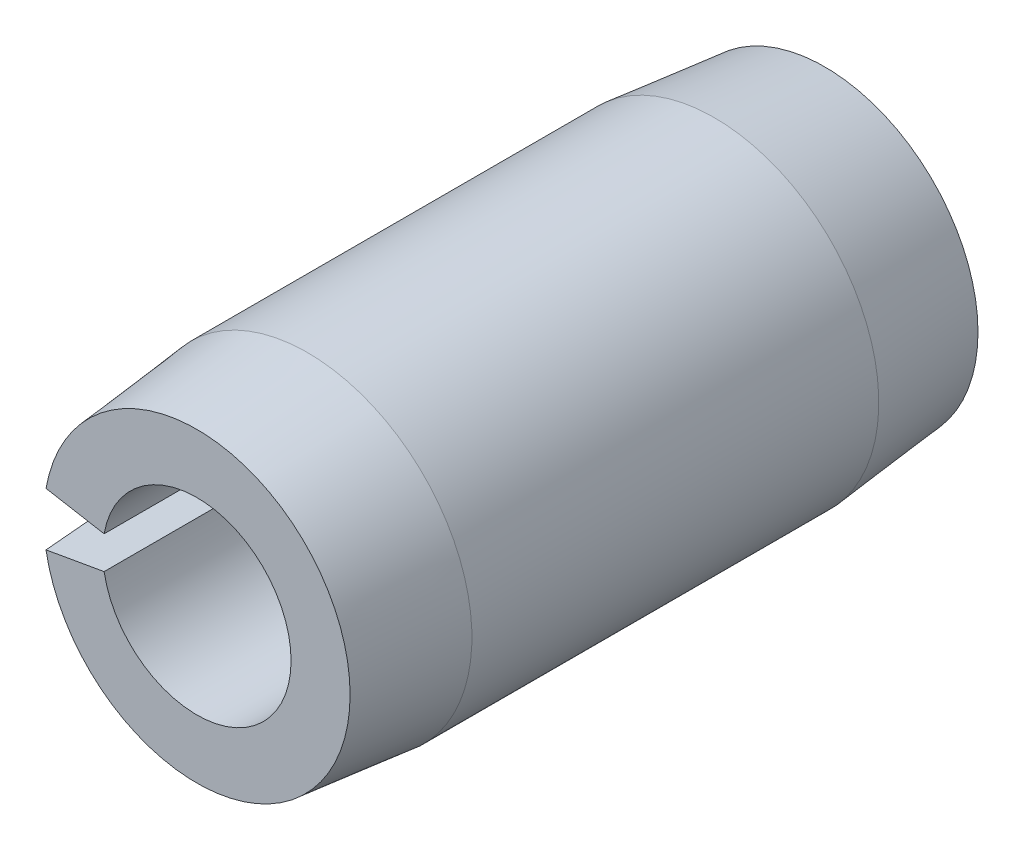
SolidWorks part; units mm, degrees
material "AISI Type 316L stainless steel"
ref_plane "Front Plane" through (0, 0, 0) normal (0, 0, 1) x (1, 0, 0)
ref_plane "Top Plane" through (0, 0, 0) normal (0, 1, 0) x (1, 0, 0)
ref_plane "Right Plane" through (0, 0, 0) normal (1, 0, 0) x (0, 0, -1)
sketch "Sketch1" plane through (0, 0, 0) normal (0, 0, 1) x (1, 0, 0)
  line L0 (0.9525, 0) -> (1.6637, 0) construction
  line L1 (-1.6384, 0.2889) -> (-0.938, 0.1654)
  line L2 (-0.938, -0.1654) -> (-1.6384, -0.2889)
  arc A0 (-1.6384, -0.2889) -> (-1.6384, 0.2889) centre (0, 0) ccw
  arc A1 (-0.938, -0.1654) -> (-0.938, 0.1654) centre (0, 0) ccw
  dimension "OD" = 3.3274
  dimension "Wall thickness" = 0.7112
  dimension "D3" = 20
extrude "Extrude1" add sketch "Sketch1" along normal mid plane 6.35
sketch "Sketch2" plane through (0, 0, 0) normal (1, 0, 0) x (0, 0, -1)
  line L0 (0, -1.6637) -> (0, 1.6637) construction
  line L1 (3.175, 0) -> (-3.175, 0) construction
  line L2 (3.175, -0.9525) -> (3.175, 0.9525) construction
  line L3 (3.175, 1.6637) -> (-3.175, 1.6637) construction
  line L4 (3.175, 1.6637) -> (3.175, 1.5494)
  line L5 (3.175, 1.5494) -> (2.0574, 1.6637)
  line L6 (2.0574, 1.6637) -> (3.175, 1.6637)
  line L7 (3.175, -1.6637) -> (3.175, 1.6637) construction
  line L8 (-2.0574, 1.6637) -> (-3.175, 1.6637)
  line L9 (-3.175, 1.5494) -> (-2.0574, 1.6637)
  line L10 (-3.175, 1.6637) -> (-3.175, 1.5494)
  line L11 (2.0574, -1.6637) -> (3.175, -1.6637) construction
  line L12 (3.175, -1.5494) -> (2.0574, -1.6637) construction
  line L13 (3.175, -1.6637) -> (3.175, -1.5494) construction
  dimension "B" = 3.0988
  dimension "Chamfer max" = 1.1176
revolve "Cut-Revolve1" cut sketch "Sketch2" angle 360 about L1
sketch "Sketch3" plane through (0, 0, 0) normal (0, 0, 1) x (1, 0, 0)
  line L0 (0.9525, 0) -> (1.6637, 0) construction
  line L1 (0.9525, 0) -> (1.6637, 0)
  circle A0 centre (0, 0) radius 1.6637
  circle A1 centre (0, 0) radius 0.9525
  arc A2 (-1.6384, -0.2889) -> (-1.6384, 0.2889) centre (0, 0) ccw construction
  arc A3 (-0.938, -0.1654) -> (-0.938, 0.1654) centre (0, 0) ccw construction
